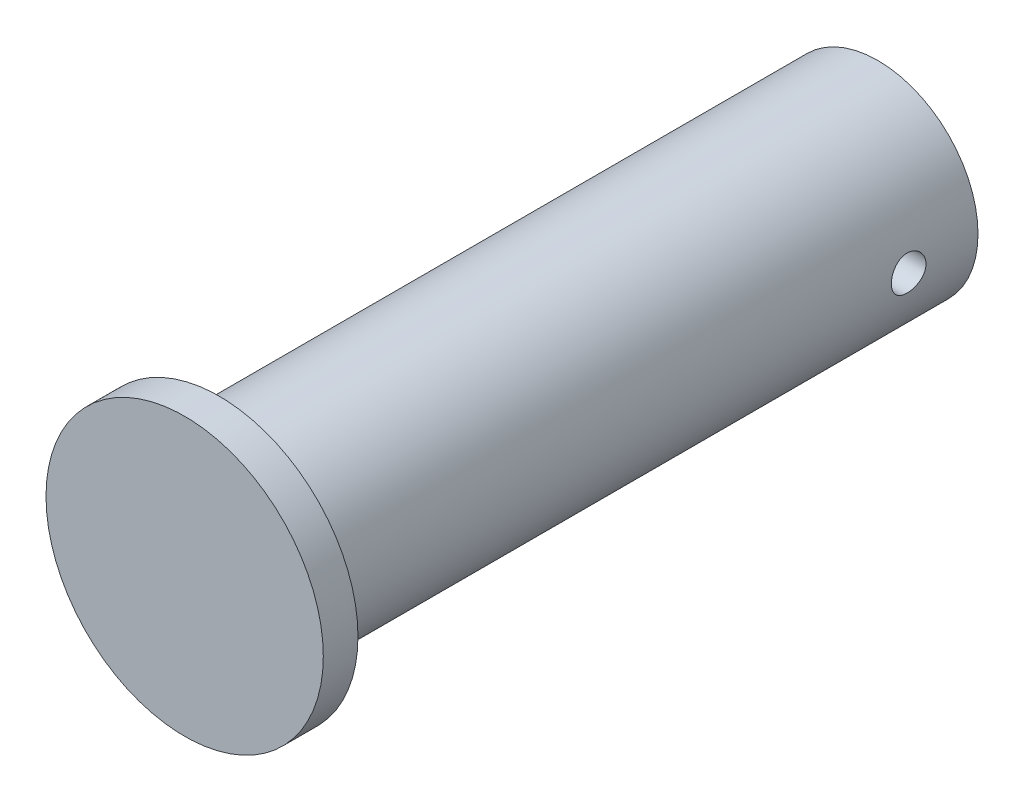
SolidWorks part; units mm, degrees
ref_plane "前视基准面" through (0, 0, 0) normal (0, 0, 1) x (1, 0, 0)
ref_plane "上视基准面" through (0, 0, 0) normal (0, 1, 0) x (1, 0, 0)
ref_plane "右视基准面" through (0, 0, 0) normal (1, 0, 0) x (0, 0, -1)
other "Configuration Table"
sketch "草图1" plane through (0, 0, 0) normal (0, 0, 1) x (1, 0, 0)
  circle A0 centre (0, 0) radius 14.44
  dimension "D1" = 28.88
extrude "凸台-拉伸1" add sketch "草图1" along normal blind 100
sketch "草图3" plane through (0, 0, 100) normal (0, 0, 1) x (1, 0, 0)
  circle A0 centre (0, 0) radius 20
  dimension "D1" = 40
extrude "凸台-拉伸3" add sketch "草图3" against normal blind 5
sketch "草图4" plane through (0, 0, 0) normal (1, 0, 0) x (0, 0, -1)
  line L0 (0, -14.44) -> (0, 14.44) construction
  circle A0 centre (-10, 0) radius 2.5
  dimension "D1" = 5
  dimension "D2" = 10
extrude "切除-拉伸1" cut sketch "草图4" against normal through all both and the other way through all
